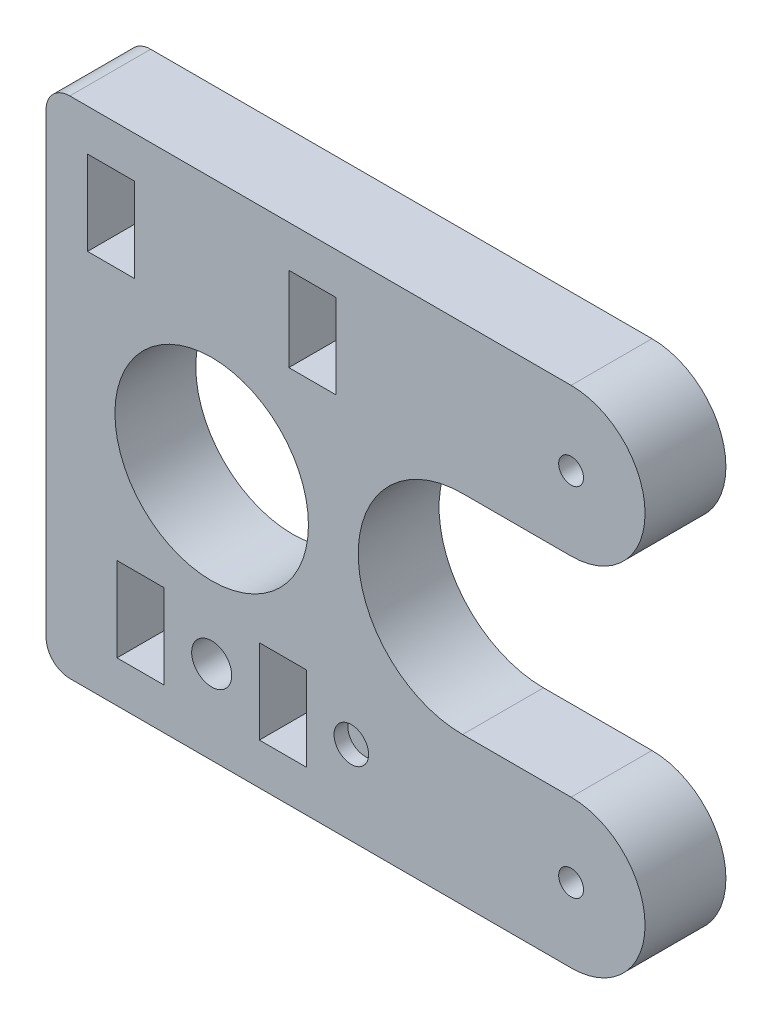
SolidWorks part; units mm, degrees
material "Acrylic (Medium-high impact)"
ref_plane "Front Plane" through (0, 0, 0) normal (0, 0, 1) x (1, 0, 0)
ref_plane "Top Plane" through (0, 0, 0) normal (0, 1, 0) x (1, 0, 0)
ref_plane "Right Plane" through (0, 0, 0) normal (1, 0, 0) x (0, 0, -1)
sketch "Sketch1" plane through (0, 0, 0) normal (0, 0, 1) x (1, 0, 0)
  line L0 (669.2168, 349.0155) -> (648.4638, 349.0155)
  line L1 (646.7465, 347.2982) -> (646.7465, 314.2328)
  line L2 (648.4638, 312.5155) -> (669.2168, 312.5155)
  line L3 (653.1465, 339.9155) -> (653.1465, 346.0155)
  line L4 (653.1465, 346.0155) -> (649.7465, 346.0155)
  line L5 (649.7465, 346.0155) -> (649.7465, 339.9155)
  line L6 (649.7465, 339.9155) -> (653.1465, 339.9155)
  line L7 (651.8765, 315.5155) -> (655.2765, 315.5155)
  line L8 (655.2765, 315.5155) -> (655.2765, 321.6155)
  line L9 (655.2765, 321.6155) -> (651.8765, 321.6155)
  line L10 (651.8765, 321.6155) -> (651.8765, 315.5155)
  line L11 (667.7065, 339.9155) -> (667.7065, 346.0155)
  line L12 (667.7065, 346.0155) -> (664.3065, 346.0155)
  line L13 (664.3065, 346.0155) -> (664.3065, 339.9155)
  line L14 (664.3065, 339.9155) -> (667.7065, 339.9155)
  line L15 (662.1765, 321.6155) -> (662.1765, 315.5155)
  line L16 (662.1765, 315.5155) -> (665.5765, 315.5155)
  line L17 (665.5765, 315.5155) -> (665.5765, 321.6155)
  line L18 (665.5765, 321.6155) -> (662.1765, 321.6155)
  line L19 (-318.4867, 330.7655) -> (49681.5133, 330.7655) construction
  line L21 (653.1465, 339.9155) -> (664.3065, 339.9155) construction
  line L22 (657.2765, 318.5655) -> (655.2765, 318.5655) construction
  line L23 (660.1765, 318.5655) -> (662.1765, 318.5655) construction
  line L24 (658.7265, -664.2806) -> (658.7265, 49335.7194) construction
  line L25 (669.2168, 312.5155) -> (684.7265, 312.5155)
  line L26 (669.2168, 349.0155) -> (684.7265, 349.0155)
  line L27 (684.7265, 317.8655) -> (684.7265, 330.7655) construction
  line L28 (684.7265, 330.7655) -> (684.7265, 343.6655) construction
  line L29 (684.7265, -668.8222) -> (684.7265, 49331.1778) construction
  line L30 (662.1765, 330.7655) -> (662.1765, 349.0155) construction
  line L31 (662.1765, 330.7655) -> (662.1765, 312.5155) construction
  line L32 (684.7265, 338.3155) -> (676.8765, 338.3155)
  line L33 (684.7265, 323.2155) -> (676.8765, 323.2155)
  circle A0 centre (684.7265, 343.6655) radius 0.9
  circle A1 centre (684.7265, 317.8655) radius 0.9
  arc A2 (684.7265, 312.5155) -> (684.7265, 323.2155) centre (684.7265, 317.8655) ccw
  circle A3 centre (658.7265, 318.5655) radius 1.45
  arc A4 (648.4638, 349.0155) -> (646.7465, 347.2982) centre (648.4638, 347.2982) ccw
  arc A5 (684.7265, 349.0155) -> (684.7265, 338.3155) centre (684.7265, 343.6655) cw
  arc A6 (676.8765, 338.3155) -> (676.8765, 323.2155) centre (676.8765, 330.7655) ccw
  arc A7 (646.7465, 314.2328) -> (648.4638, 312.5155) centre (648.4638, 314.2328) ccw
  circle A8 centre (658.7265, 330.7655) radius 7
  point P27 (658.7265, 339.9155)
  point P38 (669.3265, 330.7655)
  point P39 (665.7265, 330.7655)
  dimension "D5" = 2.9
  dimension "D12" = 3.6
  dimension "D13" = 14
  dimension "D14" = 1.8
  dimension "D15" = 1.7173
  dimension "D10" = 26
  dimension "D1" = 2
  dimension "D2" = 6.1
  dimension "D3" = 3.4
  dimension "D4" = 3.4
  dimension "D6" = 11.16
  dimension "D7" = 3
  dimension "D8" = 3
  dimension "D9" = 3
  dimension "D11" = 12.9
  dimension "D16" = 36.5
  dimension "D17" = 18.3
extrude "Boss-Extrude2" add sketch "Sketch1" along normal blind 5.85
sketch "Sketch2" plane through (0, 0, 5.85) normal (0, 0, 1) x (1, 0, 0)
  line L0 (-341.2735, 318.5655) -> (49658.7265, 318.5655) construction
  line L1 (665.5765, 315.5155) -> (665.5765, 321.6155) construction
  circle A0 centre (668.8265, 318.5655) radius 1.25
  point P5 (667.5765, 318.5655)
  dimension "D1" = 2.5
  dimension "D2" = 2
extrude "Cut-Extrude1" cut sketch "Sketch2" against normal blind 1
